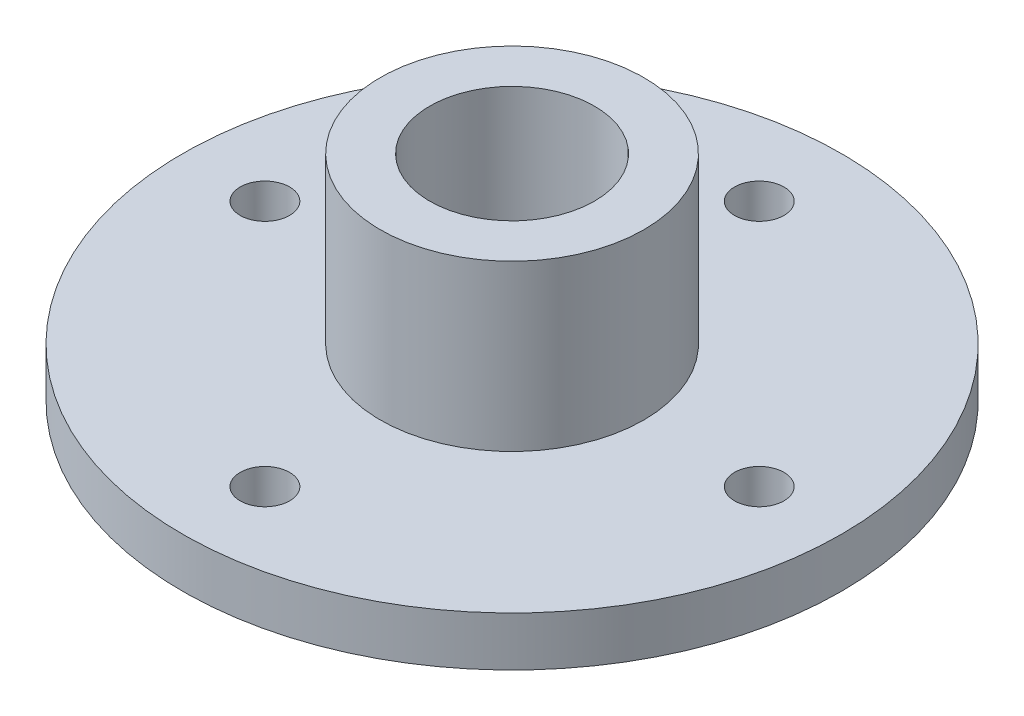
SolidWorks part; units mm, degrees
material "商用纯 CP-Ti UNS R50400 (SS)"
ref_plane "前视基准面" through (0, 0, 0) normal (0, 0, 1) x (1, 0, 0)
ref_plane "上视基准面" through (0, 0, 0) normal (0, 1, 0) x (1, 0, 0)
ref_plane "右视基准面" through (0, 0, 0) normal (1, 0, 0) x (0, 0, -1)
other "Configuration Table"
sketch "草图1" plane through (0, 0, 0) normal (0, 0, 1) x (1, 0, 0)
  line L0 (0, -573.6149) -> (0, 28107.1279) construction
  line L1 (-5, 0) -> (-20, 0)
  line L2 (-20, 0) -> (-20, 3)
  line L3 (-20, 3) -> (-8, 3)
  line L4 (-8, 3) -> (-8, 13)
  line L5 (-8, 13) -> (-5, 13)
  line L6 (-5, 13) -> (-5, 0)
  dimension "D1" = 10
  dimension "D2" = 3
  dimension "D3" = 3
  dimension "D4" = 15
  dimension "D5" = 10
revolve "旋转1" add sketch "草图1" angle 360 about L0
sketch "草图2" plane through (0, 3, 0) normal (0, 1, 0) x (1, 0, 0)
  circle A0 centre (0, 0) radius 15 construction
  circle A1 centre (0, 15) radius 1.5
  circle A2 centre (15, 0) radius 1.5
  circle A3 centre (0, -15) radius 1.5
  circle A4 centre (-15, 0) radius 1.5
  point P14 (0, 0)
  dimension "D1" = 30
  dimension "D2" = 3
  dimension "D3" = 4
extrude "切除-拉伸1" cut sketch "草图2" against normal through all both and the other way through all
